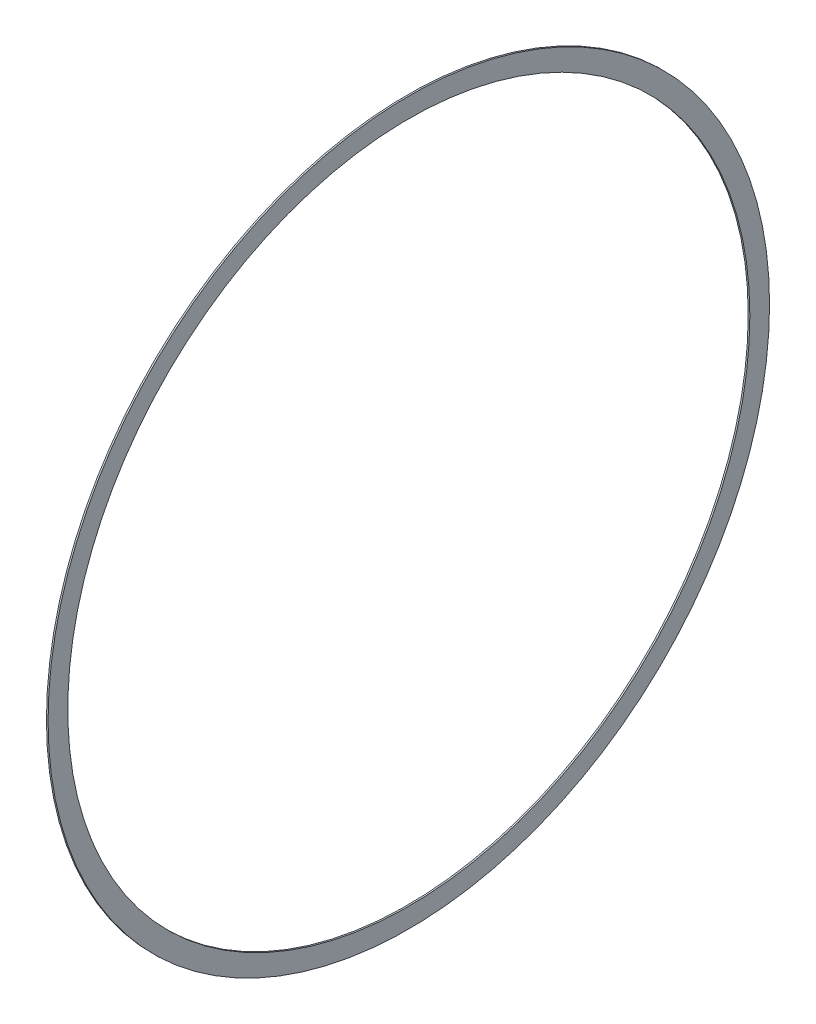
SolidWorks part; units mm, degrees
material "ASTM A36 Steel"
ref_plane "Front Plane" through (0, 0, 0) normal (0, 0, 1) x (1, 0, 0)
ref_plane "Top Plane" through (0, 0, 0) normal (0, 1, 0) x (1, 0, 0)
ref_plane "Right Plane" through (0, 0, 0) normal (1, 0, 0) x (0, 0, -1)
sketch "Sketch1" plane through (0, 0, 0) normal (1, 0, 0) x (0, 0, -1)
  circle A0 centre (0, 0) radius 1055
  circle A1 centre (0, 0) radius 1116
  dimension "D1" = 2110
  dimension "D2" = 2232
extrude "Boss-Extrude1" add sketch "Sketch1" along normal blind 5
